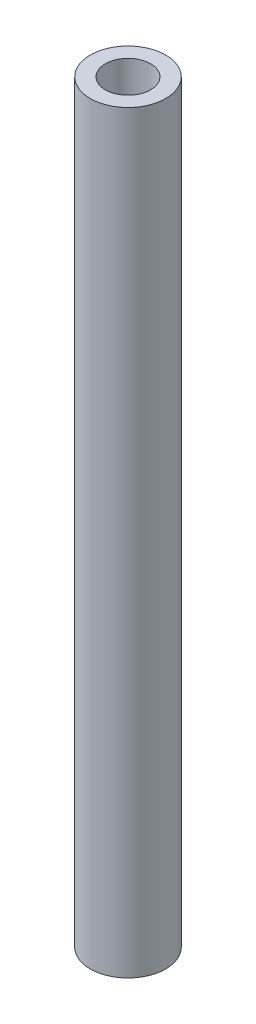
SolidWorks part; units mm, degrees
material "1060 合金"
ref_plane "前视基准面" through (0, 0, 0) normal (0, 0, 1) x (1, 0, 0)
ref_plane "上视基准面" through (0, 0, 0) normal (0, 1, 0) x (1, 0, 0)
ref_plane "右视基准面" through (0, 0, 0) normal (1, 0, 0) x (0, 0, -1)
other "Configuration Table"
sketch "草图1" plane through (0, 0, 0) normal (0, 1, 0) x (1, 0, 0)
  circle A0 centre (0, 0) radius 2.5
  circle A1 centre (0, 0) radius 1.5
  dimension "D1" = 3
  dimension "D2" = 5
extrude "凸台-拉伸1" add sketch "草图1" along normal blind 50
